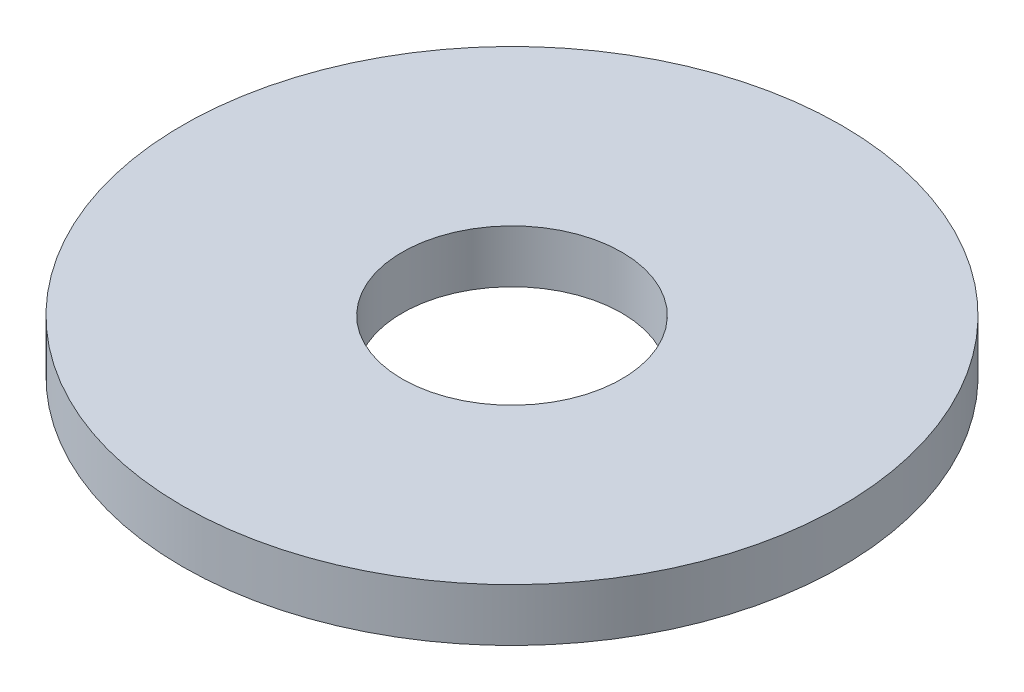
SolidWorks part; units mm, degrees
material "AISI 304"
ref_plane "前视基准面" through (0, 0, 0) normal (0, 0, 1) x (1, 0, 0)
ref_plane "上视基准面" through (0, 0, 0) normal (0, 1, 0) x (1, 0, 0)
ref_plane "右视基准面" through (0, 0, 0) normal (1, 0, 0) x (0, 0, -1)
sketch "草图1" plane through (0, 0, 0) normal (0, 1, 0) x (1, 0, 0)
  circle A0 centre (0, 0) radius 2.5
  circle A1 centre (0, 0) radius 7.5
  dimension "D1" = 5
  dimension "D2" = 15
extrude "凸台-拉伸1" add sketch "草图1" along normal blind 1.2
